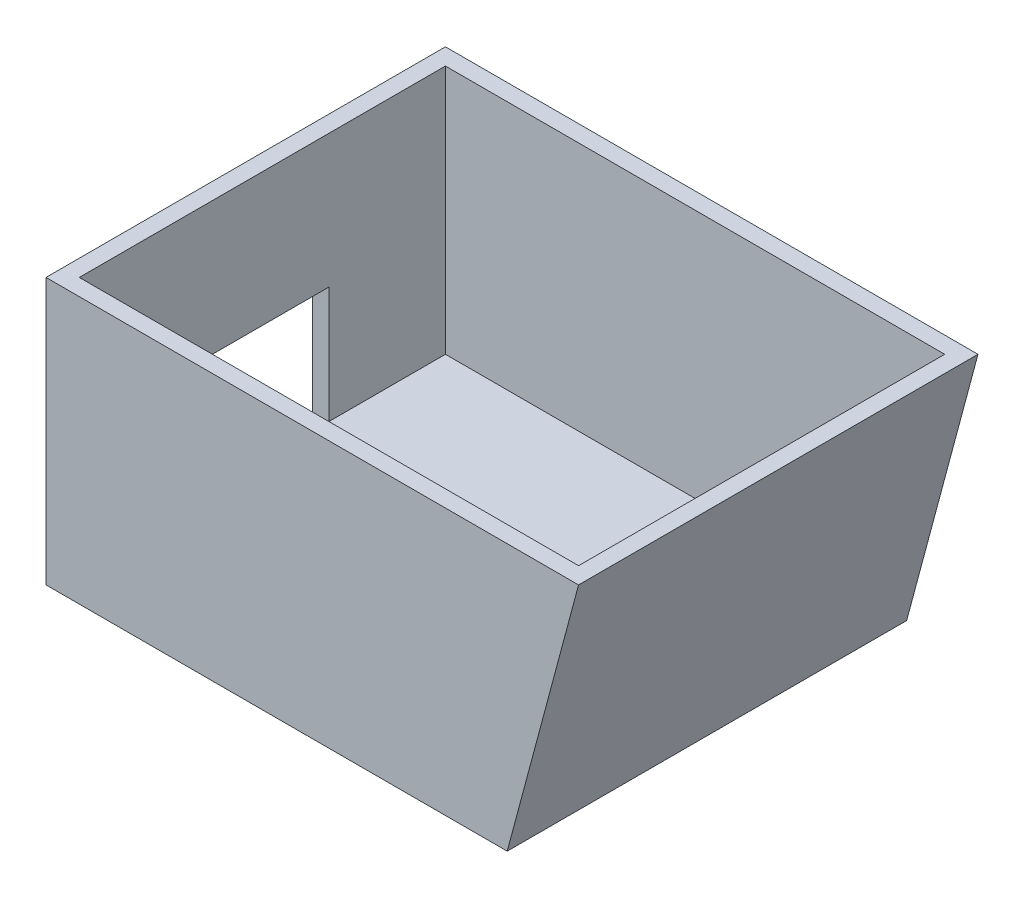
SolidWorks part; units mm, degrees
material "ABS PC"
ref_plane "Front Plane" through (0, 0, 0) normal (0, 0, 1) x (1, 0, 0)
ref_plane "Top Plane" through (0, 0, 0) normal (0, 1, 0) x (1, 0, 0)
ref_plane "Right Plane" through (0, 0, 0) normal (1, 0, 0) x (0, 0, -1)
sketch "Sketch10" plane through (0, 0, 0) normal (0, 1, 0) x (1, 0, 0)
  line L1 (-50.8, 38.1) -> (50.8, 38.1)
  line L2 (-50.8, 38.1) -> (-50.8, -38.1)
  line L3 (-50.8, -38.1) -> (50.8, -38.1)
  line L4 (50.8, 38.1) -> (50.8, -38.1)
  line L5 (-50.8, 38.1) -> (50.8, -38.1) construction
  line L6 (-50.8, -38.1) -> (50.8, 38.1) construction
  point P0 (0, 0)
  point P6 (0, 0)
  dimension "D1" = 76.2
  dimension "D2" = 101.6
extrude "Boss-Extrude4" add sketch "Sketch10" along normal blind 50.8
sketch "Sketch12" plane through (0, 0, 0) normal (0, -1, 0) x (1, 0, 0)
  line L0 (-50.8, 38.1) -> (50.8, 38.1) construction
  line L1 (-47.625, 34.925) -> (47.625, 34.925)
  line L2 (-47.625, 34.925) -> (-47.625, -34.925)
  line L3 (-47.625, -34.925) -> (47.625, -34.925)
  line L4 (47.625, 34.925) -> (47.625, -34.925)
  line L5 (-47.625, 34.925) -> (47.625, -34.925) construction
  line L6 (-47.625, -34.925) -> (47.625, 34.925) construction
  line L7 (50.8, 38.1) -> (50.8, -38.1) construction
  point P0 (0, 0)
  dimension "D1" = 3.175
  dimension "D2" = 3.175
hole_wizard "#6 Clearance Hole1" positions "Sketch14" profile "Sketch15" hole size "#6" standard "ANSI Inch"
sketch "Sketch14" plane through (0, 50.8, 0) normal (0, 1, 0) x (1, 0, 0)
  line L0 (50.8, -38.1) -> (50.8, 38.1) construction
  point P0 (44.45, 5.5562)
  point P2 (44.45, -5.5562)
  dimension "D1" = 11.1125
  dimension ".25" = 6.35
  dimension "D3" = 5.5562
sketch "Sketch15" plane through (44.45, 50.8, -5.5562) normal (1, 0, 0) x (0, 0, 1)
  line L0 (0, 0) -> (0, 13.8408)
  line L1 (0, 13.8408) -> (1.8986, 12.7)
  line L2 (1.8986, 12.7) -> (1.8986, 0)
  line L5 (1.8986, 0) -> (0, 0)
  line L10 (0, 13.8408) -> (-1.8987, 12.7) construction
  line L11 (0, -6.35) -> (0, 107.95) construction
  dimension "Hole Dia." = 3.7973
  dimension "Hole Depth" = 12.7
  dimension "Drill Angle" = 118
sketch "Sketch16" plane through (0, 0, 38.1) normal (0, 0, 1) x (1, 0, 0)
  line L1 (34.0132, 0) -> (47.625, 50.8)
  line L2 (-50.8, 50.8) -> (50.8, 50.8) construction
  line L5 (47.625, 50.8) -> (50.8, 50.8)
  line L8 (-50.8, 0) -> (50.8, 0) construction
  line L9 (37.1882, 0) -> (34.0132, 0)
  line L10 (50.8, 50.8) -> (37.1882, 0)
  line L11 (50.8, 50.8) -> (50.8, 0) construction
  dimension "D1" = 15
  dimension "D2" = 3.175
sketch "Sketch17" plane through (0, 0, 38.1) normal (0, 0, 1) x (1, 0, 0)
  line L0 (50.8, 50.8) -> (37.1882, 0) construction
  line L1 (50.8, 0) -> (50.8, 50.8)
  line L2 (37.1882, 0) -> (50.8, 0)
  line L4 (47.625, 50.8) -> (34.0132, 0)
  line L5 (50.8, 50.8) -> (47.625, 50.8)
  line L6 (37.1882, 0) -> (50.8, 50.8)
  line L7 (34.0132, 0) -> (37.1882, 0)
  line L10 (37.1882, 0) -> (50.8, 50.8)
  dimension "D1" = 0
extrude "Cut-Extrude6" cut sketch "Sketch17" against normal through all
sketch "Sketch18" plane through (0, 0, 38.1) normal (0, 0, 1) x (1, 0, 0)
  line L4 (47.625, 50.8) -> (34.0132, 0)
  line L5 (50.8, 50.8) -> (47.625, 50.8)
  line L6 (37.1882, 0) -> (50.8, 50.8)
  line L7 (34.0132, 0) -> (37.1882, 0)
  line L8 (47.625, 50.8) -> (34.0132, 0)
  line L9 (50.8, 50.8) -> (47.625, 50.8)
  line L10 (37.1882, 0) -> (50.8, 50.8)
  line L11 (34.0132, 0) -> (37.1882, 0)
  dimension "D1" = 0
extrude "Boss-Extrude6" add sketch "Sketch18" against normal blind 73.025
sketch "Sketch19" plane through (0, 50.8, 0) normal (0, 1, 0) x (1, 0, 0)
  line L4 (-47.625, -34.925) -> (47.625, -34.925)
  line L5 (47.625, -34.925) -> (47.625, 34.925)
  line L6 (47.625, 34.925) -> (-47.625, 34.925)
  line L7 (-47.625, 34.925) -> (-47.625, -34.925)
  line L8 (-47.625, -34.925) -> (47.625, -34.925)
  line L9 (47.625, -34.925) -> (47.625, 34.925)
  line L10 (47.625, 34.925) -> (-47.625, 34.925)
  line L11 (-47.625, 34.925) -> (-47.625, -34.925)
  dimension "D1" = 0
extrude "Cut-Extrude7" cut sketch "Sketch19" against normal blind 47.625
sketch "Sketch20" plane through (0, 0, 38.1) normal (0, 0, 1) x (1, 0, 0)
  line L4 (47.625, 50.8) -> (34.0132, 0)
  line L5 (34.0132, 0) -> (37.1882, 0)
  line L6 (37.1882, 0) -> (50.8, 50.8)
  line L7 (50.8, 50.8) -> (47.625, 50.8)
  line L8 (47.625, 50.8) -> (34.0132, 0)
  line L9 (34.0132, 0) -> (37.1882, 0)
  line L10 (37.1882, 0) -> (50.8, 50.8)
  line L11 (50.8, 50.8) -> (47.625, 50.8)
  dimension "D1" = 0
extrude "Boss-Extrude7" add sketch "Sketch20" against normal blind 73.025
sketch "Sketch21" plane through (0, 0, 0) normal (0, -1, 0) x (1, 0, 0)
  line L0 (-50.8, -38.1) -> (-50.8, 38.1) construction
  line L1 (-50.8, 12.7) -> (-25.4, 12.7)
  line L2 (-50.8, 12.7) -> (-50.8, -12.7)
  line L3 (-50.8, -12.7) -> (-25.4, -12.7)
  line L4 (-25.4, 12.7) -> (-25.4, -12.7)
  line L5 (-25.4, 0) -> (-50.8, 0) construction
  line L6 (37.1882, -38.1) -> (-50.8, -38.1) construction
  dimension "D1" = 25.4
  dimension "D2" = 25.4
  dimension "D3" = 38.1
extrude "Cut-Extrude8" cut sketch "Sketch21" against normal blind 25.4
